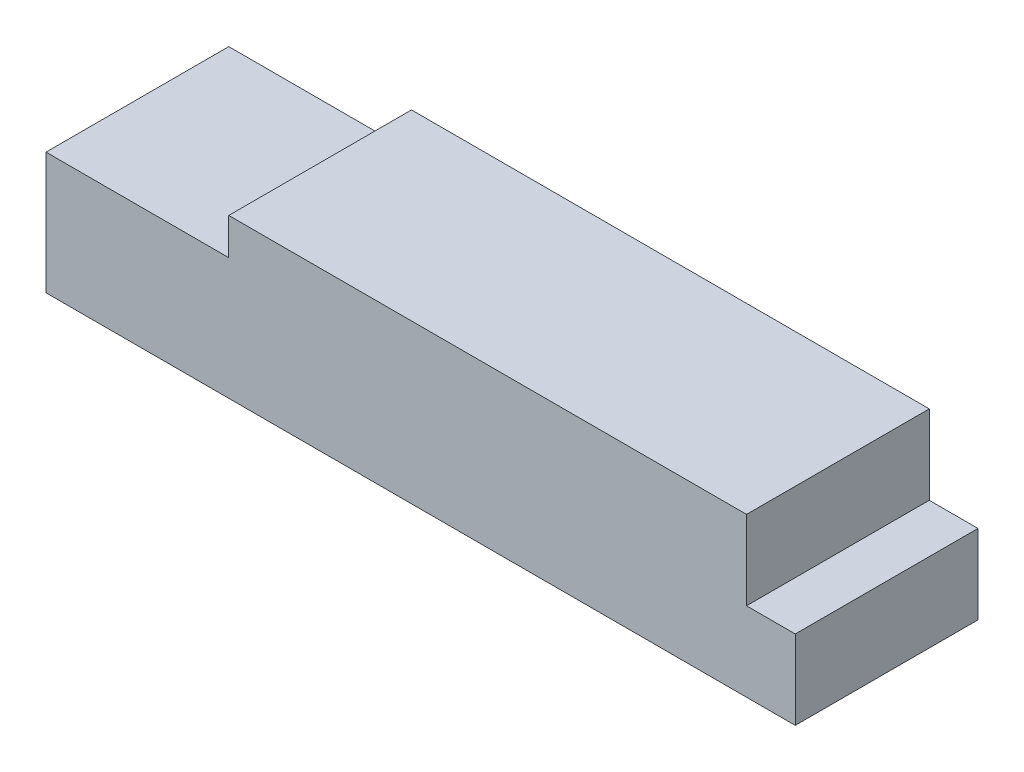
SolidWorks part; units mm, degrees
ref_plane "Piano frontale" through (0, 0, 0) normal (0, 0, 1) x (1, 0, 0)
ref_plane "Piano superiore" through (0, 0, 0) normal (0, 1, 0) x (1, 0, 0)
ref_plane "Piano destro" through (0, 0, 0) normal (1, 0, 0) x (0, 0, -1)
sketch "Schizzo1" plane through (0, 0, 0) normal (0, 0, 1) x (1, 0, 0)
  line L0 (0, 0) -> (123, 0)
  line L1 (123, 0) -> (123, 13)
  line L2 (123, 13) -> (115, 13)
  line L3 (115, 13) -> (115, 26)
  line L4 (115, 26) -> (30, 26)
  line L5 (30, 26) -> (30, 20)
  line L6 (30, 20) -> (0, 20)
  line L7 (0, 20) -> (0, 0)
  point P7 (-15.0897, -5.1744)
  point P9 (-14.1594, -1.4535)
  point P10 (-15.2059, -5.0581)
  point P11 (-25.9036, -12.2674)
  point P12 (-24.5083, -11.686)
  point P13 (-57.6478, -11.9186)
  point P14 (-23.8106, -12.8488)
  point P15 (-23.2292, -17.3837)
  point P16 (-16.3687, -11.5698)
  point P17 (-49.1736, -11.4158)
  point P18 (0, 0)
  point P20 (0, 0)
  point P21 (0, 0)
  point P22 (0, 0)
  point P23 (115, 26)
  point P24 (1.1516, 0.4214)
  point P25 (0, 0)
  point P26 (0, 0)
  point P28 (0, 0)
  dimension "D1" = 6
  dimension "D2" = 8
  dimension "D3" = 123
  dimension "D4" = 13
  dimension "D5" = 30
  dimension "D6" = 26
extrude "Estrusione-Estrusione1" add sketch "Schizzo1" along normal mid plane 30
